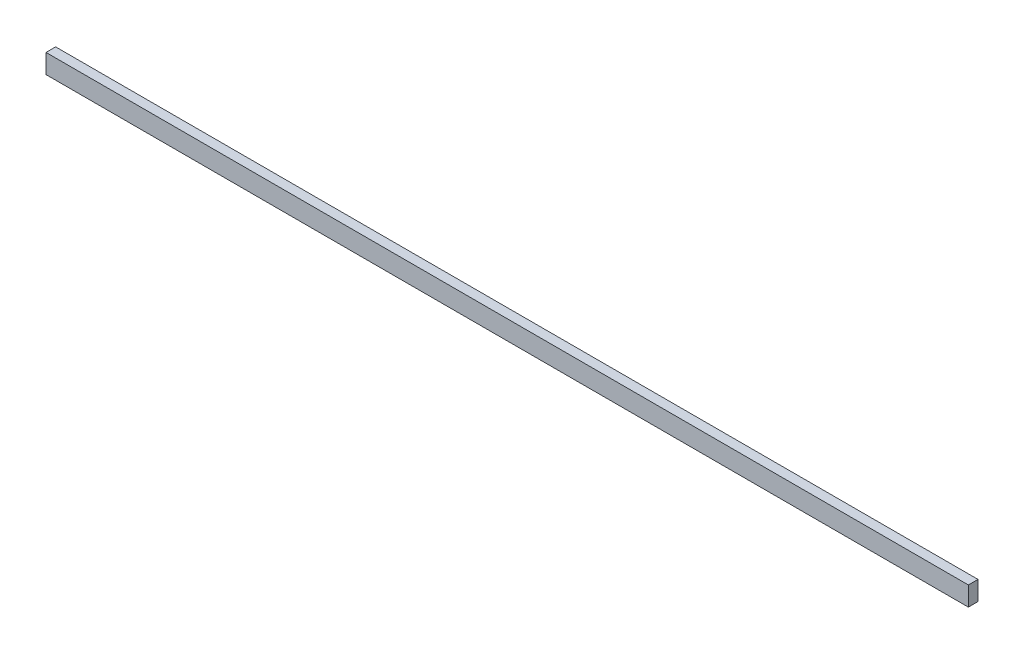
SolidWorks part; units mm, degrees
ref_plane "Front Plane" through (0, 0, 0) normal (0, 0, 1) x (1, 0, 0)
ref_plane "Top Plane" through (0, 0, 0) normal (0, 1, 0) x (1, 0, 0)
ref_plane "Right Plane" through (0, 0, 0) normal (1, 0, 0) x (0, 0, -1)
sketch "Sketch2" plane through (0, 0, 0) normal (0, 1, 0) x (1, 0, 0)
  line L1 (-228.6, 2.3876) -> (228.6, 2.3876)
  line L2 (-228.6, 2.3876) -> (-228.6, -2.3876)
  line L3 (-228.6, -2.3876) -> (228.6, -2.3876)
  line L4 (228.6, 2.3876) -> (228.6, -2.3876)
  line L5 (-228.6, 2.3876) -> (228.6, -2.3876) construction
  line L6 (-228.6, -2.3876) -> (228.6, 2.3876) construction
  point P0 (0, 0)
  dimension "D1" = 457.2
  dimension "D2" = 4.7752
extrude "Boss-Extrude1" add sketch "Sketch2" along normal blind 9.525
sketch "Sketch3" plane through (0, 9.525, 0) normal (0, 1, 0) x (1, 0, 0)
  line L0 (0, 2.3876) -> (0, -2.3876)
  line L1 (228.6, 2.3876) -> (-228.6, 2.3876) construction
  line L2 (-228.6, -2.3876) -> (228.6, -2.3876) construction
  line L3 (-228.6, 2.3876) -> (-228.6, -2.3876) construction
  line L5 (228.6, -0.2032) -> (-228.6, -0.2032)
  line L6 (228.6, -0.2032) -> (228.6, 0.2032)
  line L7 (228.6, 0.2032) -> (-228.6, 0.2032)
  line L8 (-228.6, -0.2032) -> (-228.6, 0.2032)
  line L9 (228.6, -0.2032) -> (-228.6, 0.2032) construction
  line L10 (228.6, 0.2032) -> (-228.6, -0.2032) construction
  line L11 (0, -2.3876) -> (228.6, -0.2032)
  line L12 (228.6, 0.2032) -> (0, 2.3876)
  line L13 (0, 2.3876) -> (-228.6, 0.2032)
  line L14 (-228.6, -0.2032) -> (0, -2.3876)
  point P6 (0, 0)
  dimension "D1" = 0.4064
ref_plane "Plane1" through (0, 152.4, 0) normal (0, 1, 0) x (1, 0, 0)
sketch "Sketch5" plane through (0, 152.4, 0) normal (0, 1, 0) x (1, 0, 0)
  line L0 (228.6, 0) -> (180.975, 0)
  line L1 (180.975, 0) -> (130.175, 0)
  line L2 (130.175, -0.2032) -> (155.575, -2.3876)
  line L3 (-228.6, -2.3876) -> (228.6, -2.3876) construction
  line L4 (130.175, -0.2032) -> (180.975, -0.2032)
  line L5 (155.575, -2.3876) -> (180.975, -0.2032)
  line L6 (130.175, -0.2032) -> (130.175, 0.2032)
  line L7 (130.175, 0.2032) -> (180.975, 0.2032)
  line L8 (180.975, -0.2032) -> (180.975, 0.2032)
  line L10 (228.6, -0.2032) -> (228.6, 0.2032) construction
  point P11 (180.975, 0)
  dimension "D1" = 47.625
  dimension "D2" = 50.8
  dimension "D3" = 0.4064
